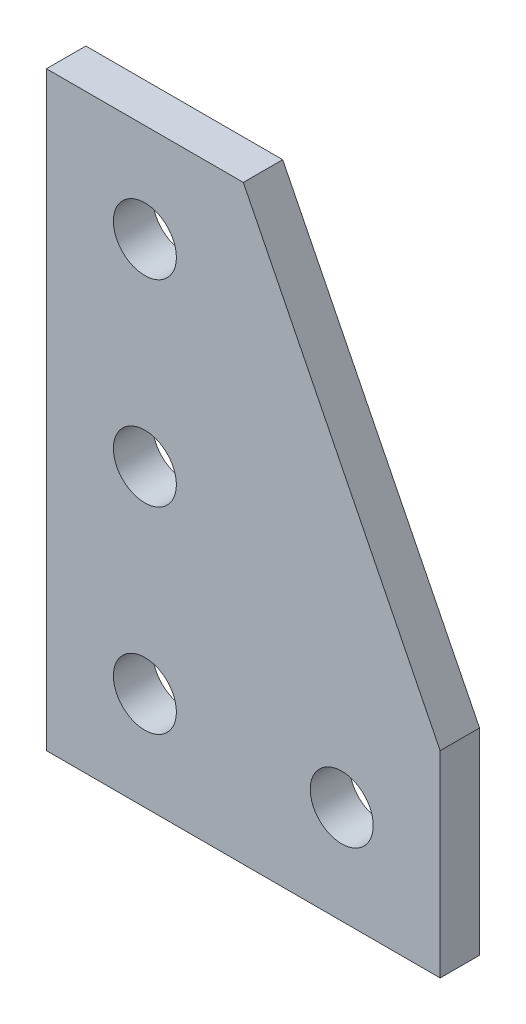
SolidWorks part; units mm, degrees
ref_plane "正面" through (0, 0, 0) normal (0, 0, 1) x (1, 0, 0)
ref_plane "平面" through (0, 0, 0) normal (0, 1, 0) x (1, 0, 0)
ref_plane "右側面" through (0, 0, 0) normal (1, 0, 0) x (0, 0, -1)
sketch "ｽｹｯﾁ1" plane through (0, 0, 0) normal (0, 0, 1) x (1, 0, 0)
  line L0 (0, 0) -> (0, 30)
  line L1 (0, 30) -> (10, 30)
  line L2 (10, 30) -> (20, 10)
  line L3 (20, 10) -> (20, 0)
  line L4 (20, 0) -> (0, 0)
  circle A0 centre (5, 25) radius 1.6
  circle A1 centre (5, 15) radius 1.6
  circle A2 centre (5, 5) radius 1.6
  circle A3 centre (15, 5) radius 1.6
  dimension "D5" = 3.2
  dimension "D6" = 3.2
  dimension "D7" = 3.2
  dimension "D8" = 3.2
  dimension "D9" = 5
  dimension "D10" = 5
  dimension "D11" = 5
  dimension "D12" = 5
  dimension "D13" = 5
  dimension "D14" = 15
  dimension "D15" = 5
  dimension "D16" = 5
  dimension "D1" = 10
  dimension "D2" = 30
  dimension "D3" = 20
  dimension "D4" = 10
extrude "ﾎﾞｽ - 押し出し1" add sketch "ｽｹｯﾁ1" along normal blind 2
